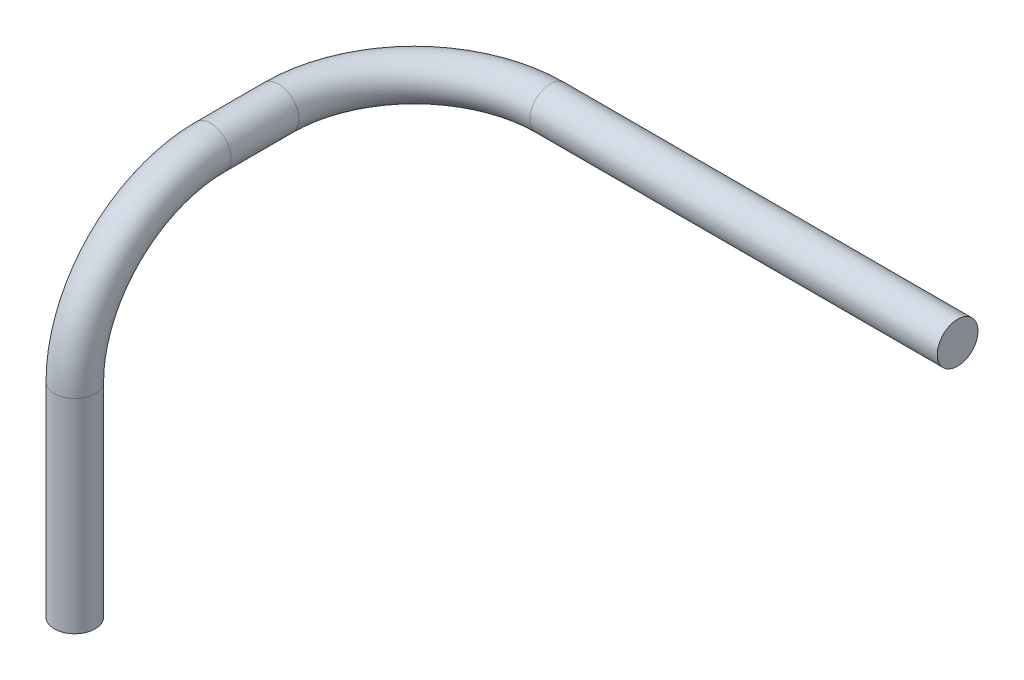
SolidWorks part; units mm, degrees
ref_plane "Plan de face" through (0, 0, 0) normal (0, 0, 1) x (1, 0, 0)
ref_plane "Plan de dessus" through (0, 0, 0) normal (0, 1, 0) x (1, 0, 0)
ref_plane "Plan de droite" through (0, 0, 0) normal (1, 0, 0) x (0, 0, -1)
sketch3d "Esquisse3D1"
  line L0 (0, 0, 0) -> (0, 15, 0)
  line L1 (0, 25, -10) -> (0, 25, -15)
  line L2 (10, 25, -25) -> (40, 25, -25)
  arc A0 (0, 15, 0) -> (0, 25, -10) centre (0, 15, -10) ccw
  arc A1 (0, 25, -15) -> (10, 25, -25) centre (10, 25, -15) ccw
  point P6 (0, 25, 0)
  point P7 (-10, 15, -10)
  point P9 (0, 0, 0)
  point P12 (0, 25, -25)
  point P13 (10, 15, -15)
  dimension "D1" = 10
  dimension "D4" = 10
  dimension "D2" = 15
  dimension "D3" = 15
  dimension "D5" = 30
sweep "Balayage1" add path "Esquisse3D1" circular profile diameter 3 parameters "D3"=3
